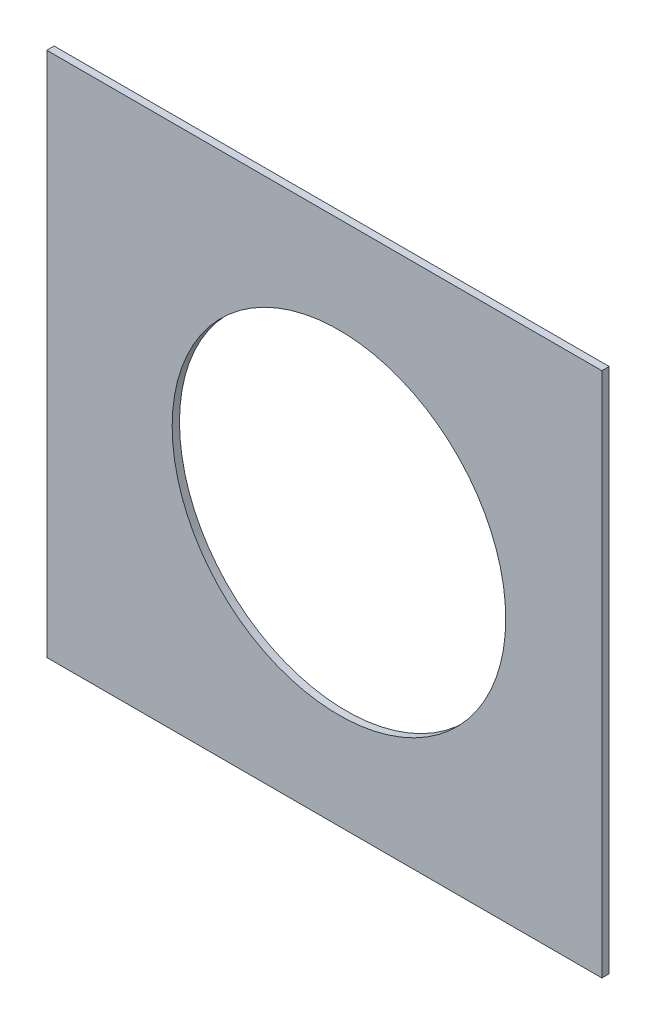
SolidWorks part; units mm, degrees
ref_plane "Front Plane" through (0, 0, 0) normal (0, 0, 1) x (1, 0, 0)
ref_plane "Top Plane" through (0, 0, 0) normal (0, 1, 0) x (1, 0, 0)
ref_plane "Right Plane" through (0, 0, 0) normal (1, 0, 0) x (0, 0, -1)
sketch "Sketch2" plane through (0, 0, 0) normal (0, 0, 1) x (1, 0, 0)
  line L1 (-127, 114.3) -> (114.3, 114.3)
  line L2 (-127, 114.3) -> (-127, -114.3)
  line L3 (-127, -114.3) -> (114.3, -114.3)
  line L4 (114.3, 114.3) -> (114.3, -114.3)
  circle A0 centre (0, 0) radius 72.5
  circle A1 centre (0, 0) radius 100
  dimension "D1" = 145
  dimension "D2" = 200
  dimension "D3" = 114.3
  dimension "D4" = 127
  dimension "D5" = 114.3
  dimension "D6" = 114.3
extrude "Boss-Extrude1" add sketch "Sketch2" along normal blind 3.175 contours L4 L1 L2 L3 A1 | A1 A0
